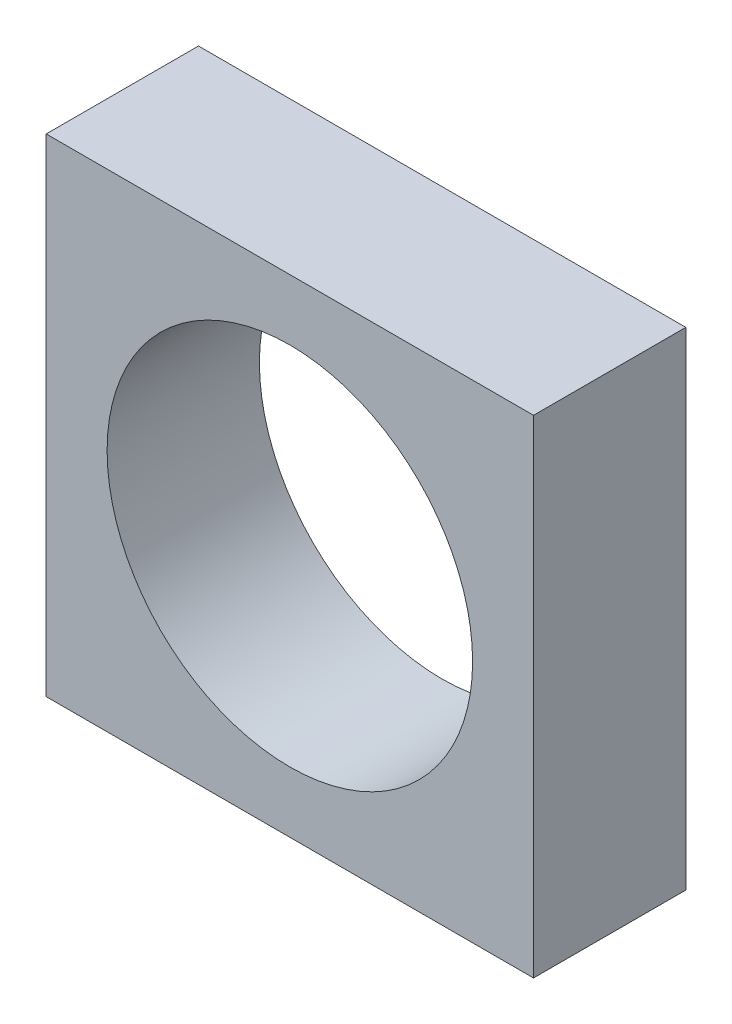
SolidWorks part; units mm, degrees
material "6061 合金"
ref_plane "前视基准面" through (0, 0, 0) normal (0, 0, 1) x (1, 0, 0)
ref_plane "上视基准面" through (0, 0, 0) normal (0, 1, 0) x (1, 0, 0)
ref_plane "右视基准面" through (0, 0, 0) normal (1, 0, 0) x (0, 0, -1)
sketch "草图1" plane through (0, 0, 0) normal (0, 0, 1) x (1, 0, 0)
  line L1 (8, 8) -> (-8, 8)
  line L2 (8, 8) -> (8, -8)
  line L3 (8, -8) -> (-8, -8)
  line L4 (-8, 8) -> (-8, -8)
  line L5 (8, 8) -> (-8, -8) construction
  line L6 (8, -8) -> (-8, 8) construction
  circle A0 centre (0, 0) radius 6
  dimension "D1" = 12
  dimension "D2" = 16
extrude "凸台-拉伸1" add sketch "草图1" along normal blind 5
